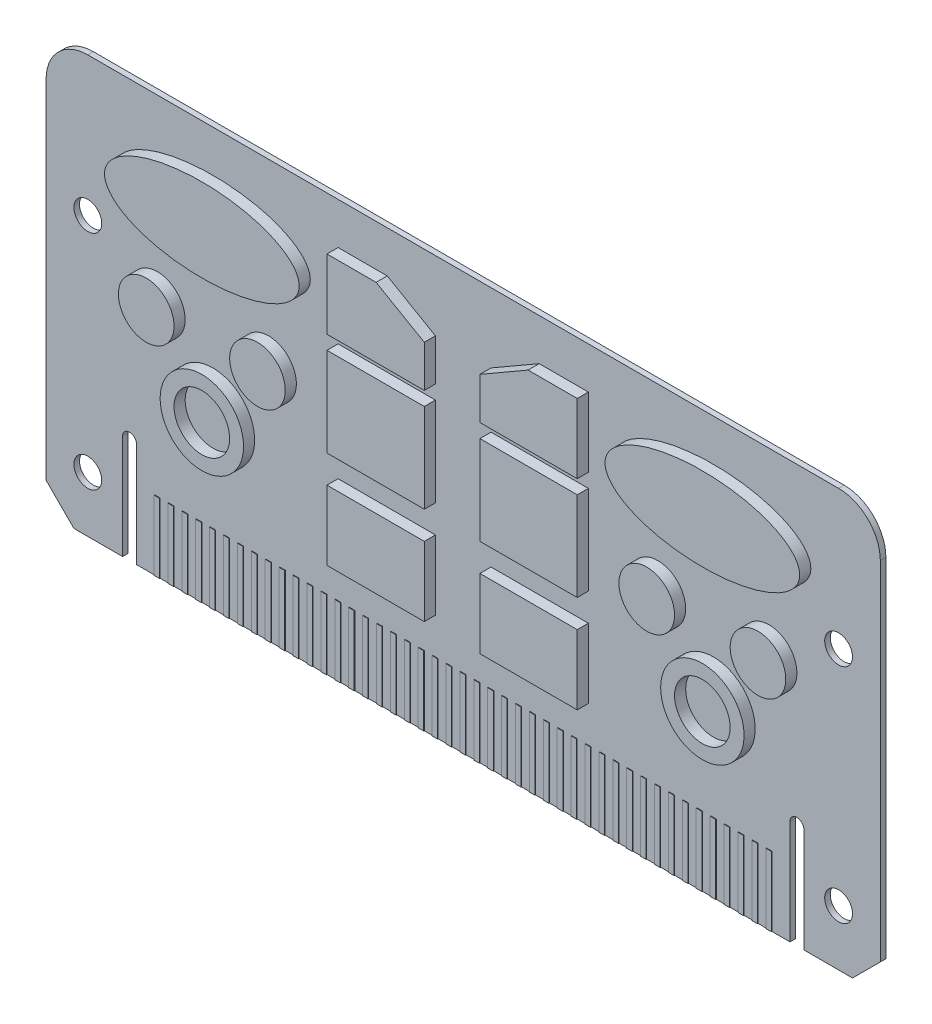
SolidWorks part; units mm, degrees
ref_plane "Front" through (0, 0, 0) normal (0, 0, 1) x (1, 0, 0)
ref_plane "Top" through (0, 0, 0) normal (0, 1, 0) x (1, 0, 0)
ref_plane "Right" through (0, 0, 0) normal (1, 0, 0) x (0, 0, -1)
sketch "Sketch1" plane through (0, 0, 0) normal (0, 0, 1) x (1, 0, 0)
  line L0 (0, 0) -> (-300, 0)
  line L1 (-300, 0) -> (-300, 150)
  line L2 (-300, 150) -> (0, 150)
  line L3 (0, 150) -> (0, 0)
  dimension "D1" = 150
  dimension "D2" = 300
extrude "PCB Base" add sketch "Sketch1" against normal mid plane 2
sketch "Sketch3" plane through (0, 0, 1) normal (0, 0, 1) x (1, 0, 0)
  line L0 (-270, -37.5) -> (-270, 37.5) construction
  line L2 (-300, 0) -> (0, 0) construction
  line L3 (-272.5, -37.5) -> (-272.5, 37.5)
  line L4 (-267.5, -37.5) -> (-267.5, 37.5)
  line L5 (-300, 150) -> (-300, 0) construction
  line L6 (-150, 150) -> (-150, 0) construction
  line L7 (0, 150) -> (-300, 150) construction
  line L8 (-30, -37.5) -> (-30, 37.5) construction
  line L9 (-27.5, -37.5) -> (-27.5, 37.5)
  line L10 (-32.5, -37.5) -> (-32.5, 37.5)
  arc A0 (-272.5, -37.5) -> (-267.5, -37.5) centre (-270, -37.5) ccw
  arc A1 (-267.5, 37.5) -> (-272.5, 37.5) centre (-270, 37.5) ccw
  arc A2 (-27.5, -37.5) -> (-32.5, -37.5) centre (-30, -37.5) cw
  arc A3 (-32.5, 37.5) -> (-27.5, 37.5) centre (-30, 37.5) cw
  point P4 (-270, 0)
  point P17 (-30, 0)
  dimension "D2" = 30
  dimension "D1" = 2.5
  dimension "D3" = 40
extrude "Slots" cut sketch "Sketch3" against normal up to next
sketch "Sketch2" plane through (0, 0, 0) normal (0, 0, 1) x (1, 0, 0)
  line L0 (-27.5, 0) -> (0, 0) construction
  line L1 (0, 0) -> (0, 150) construction
  line L2 (-267.5, 0) -> (-32.5, 0) construction
  line L3 (-150, 150) -> (-150, 0) construction
  line L4 (0, 150) -> (-300, 150) construction
  line L5 (-177.3205, 135) -> (-160, 125)
  line L6 (-195, 135) -> (-177.3205, 135)
  line L7 (-195, 135) -> (-195, 110)
  line L8 (-195, 110) -> (-160, 110)
  line L9 (-160, 125) -> (-160, 110)
  line L10 (-195, 105) -> (-160, 105)
  line L11 (-195, 105) -> (-195, 73)
  line L12 (-195, 73) -> (-160, 73)
  line L13 (-160, 105) -> (-160, 73)
  line L14 (-195, 63) -> (-160, 63)
  line L15 (-195, 63) -> (-195, 38)
  line L16 (-195, 38) -> (-160, 38)
  line L17 (-160, 63) -> (-160, 38)
  line L18 (-140, 63) -> (-140, 38)
  line L19 (-105, 38) -> (-140, 38)
  line L20 (-105, 63) -> (-105, 38)
  line L21 (-105, 63) -> (-140, 63)
  line L22 (-140, 105) -> (-140, 73)
  line L23 (-105, 73) -> (-140, 73)
  line L24 (-105, 105) -> (-105, 73)
  line L25 (-105, 105) -> (-140, 105)
  line L26 (-140, 125) -> (-140, 110)
  line L27 (-105, 110) -> (-140, 110)
  line L28 (-105, 135) -> (-105, 110)
  line L29 (-105, 135) -> (-122.6795, 135)
  line L30 (-122.6795, 135) -> (-140, 125)
  circle A0 centre (-260, 85) radius 10
  circle A1 centre (-220, 85) radius 10
  circle A2 centre (-240, 60) radius 15
  circle A3 centre (-240, 60) radius 10
  circle A4 centre (-60, 60) radius 10
  circle A5 centre (-60, 60) radius 15
  circle A6 centre (-80, 85) radius 10
  circle A7 centre (-40, 85) radius 10
  ellipse E0 centre (-240, 120) end of major axis (-275, 120) minor radius 15
  ellipse E1 centre (-60, 120) end of major axis (-95, 120) minor radius 15
  dimension "D1" = 70
  dimension "D3" = 240
  dimension "D5" = 220
  dimension "D6" = 40
  dimension "D7" = 85
  dimension "D8" = 20
  dimension "D11" = 30
  dimension "D12" = 5
  dimension "D2" = 30
  dimension "D4" = 120
  dimension "D9" = 240
  dimension "D10" = 60
  dimension "D13" = 160
  dimension "D14" = 15
  dimension "D15" = 135
  dimension "D16" = 195
  dimension "D17" = 105
  dimension "D18" = 10
  dimension "D19" = 32
  dimension "D20" = 25
  dimension "D21" = 110
  dimension "D22" = 120
extrude "Surface Chips" add sketch "Sketch2" along normal blind 5
mirror "Mirror Chips" about plane through (0, 0, 0) normal (0, 0, 1) of "Surface Chips"
sketch "Sketch4" plane through (0, 0, 1) normal (0, 0, 1) x (1, 0, 0)
  line L1 (-261, 0) -> (-259, 0)
  line L2 (-261, 0) -> (-261, 25)
  line L3 (-261, 25) -> (-259, 25)
  line L4 (-259, 0) -> (-259, 25)
  line L6 (-256, 25) -> (-254, 25)
  line L7 (-256, 0) -> (-256, 25)
  line L8 (-254, 0) -> (-254, 25)
  line L9 (-256, 0) -> (-254, 0)
  line L10 (-251, 25) -> (-249, 25)
  line L11 (-251, 0) -> (-251, 25)
  line L12 (-249, 0) -> (-249, 25)
  line L13 (-251, 0) -> (-249, 0)
  line L14 (-246, 25) -> (-244, 25)
  line L15 (-246, 0) -> (-246, 25)
  line L16 (-244, 0) -> (-244, 25)
  line L17 (-246, 0) -> (-244, 0)
  line L18 (-241, 25) -> (-239, 25)
  line L19 (-241, 0) -> (-241, 25)
  line L20 (-239, 0) -> (-239, 25)
  line L21 (-241, 0) -> (-239, 0)
  line L22 (-236, 25) -> (-234, 25)
  line L23 (-236, 0) -> (-236, 25)
  line L24 (-234, 0) -> (-234, 25)
  line L25 (-236, 0) -> (-234, 0)
  line L26 (-231, 25) -> (-229, 25)
  line L27 (-231, 0) -> (-231, 25)
  line L28 (-229, 0) -> (-229, 25)
  line L29 (-231, 0) -> (-229, 0)
  line L30 (-226, 25) -> (-224, 25)
  line L31 (-226, 0) -> (-226, 25)
  line L32 (-224, 0) -> (-224, 25)
  line L33 (-226, 0) -> (-224, 0)
  line L34 (-221, 25) -> (-219, 25)
  line L35 (-221, 0) -> (-221, 25)
  line L36 (-219, 0) -> (-219, 25)
  line L37 (-221, 0) -> (-219, 0)
  line L38 (-216, 25) -> (-214, 25)
  line L39 (-216, 0) -> (-216, 25)
  line L40 (-214, 0) -> (-214, 25)
  line L41 (-216, 0) -> (-214, 0)
  line L42 (-211, 25) -> (-209, 25)
  line L43 (-211, 0) -> (-211, 25)
  line L44 (-209, 0) -> (-209, 25)
  line L45 (-211, 0) -> (-209, 0)
  line L46 (-206, 25) -> (-204, 25)
  line L47 (-206, 0) -> (-206, 25)
  line L48 (-204, 0) -> (-204, 25)
  line L49 (-206, 0) -> (-204, 0)
  line L50 (-201, 25) -> (-199, 25)
  line L51 (-201, 0) -> (-201, 25)
  line L52 (-199, 0) -> (-199, 25)
  line L53 (-201, 0) -> (-199, 0)
  line L54 (-196, 25) -> (-194, 25)
  line L55 (-196, 0) -> (-196, 25)
  line L56 (-194, 0) -> (-194, 25)
  line L57 (-196, 0) -> (-194, 0)
  line L58 (-191, 25) -> (-189, 25)
  line L59 (-191, 0) -> (-191, 25)
  line L60 (-189, 0) -> (-189, 25)
  line L61 (-191, 0) -> (-189, 0)
  line L62 (-186, 25) -> (-184, 25)
  line L63 (-186, 0) -> (-186, 25)
  line L64 (-184, 0) -> (-184, 25)
  line L65 (-186, 0) -> (-184, 0)
  line L66 (-181, 25) -> (-179, 25)
  line L67 (-181, 0) -> (-181, 25)
  line L68 (-179, 0) -> (-179, 25)
  line L69 (-181, 0) -> (-179, 0)
  line L70 (-176, 25) -> (-174, 25)
  line L71 (-176, 0) -> (-176, 25)
  line L72 (-174, 0) -> (-174, 25)
  line L73 (-176, 0) -> (-174, 0)
  line L74 (-171, 25) -> (-169, 25)
  line L75 (-171, 0) -> (-171, 25)
  line L76 (-169, 0) -> (-169, 25)
  line L77 (-171, 0) -> (-169, 0)
  line L78 (-166, 25) -> (-164, 25)
  line L79 (-166, 0) -> (-166, 25)
  line L80 (-164, 0) -> (-164, 25)
  line L81 (-166, 0) -> (-164, 0)
  line L82 (-161, 25) -> (-159, 25)
  line L83 (-161, 0) -> (-161, 25)
  line L84 (-159, 0) -> (-159, 25)
  line L85 (-161, 0) -> (-159, 0)
  line L86 (-156, 25) -> (-154, 25)
  line L87 (-156, 0) -> (-156, 25)
  line L88 (-154, 0) -> (-154, 25)
  line L89 (-156, 0) -> (-154, 0)
  line L90 (-151, 25) -> (-149, 25)
  line L91 (-151, 0) -> (-151, 25)
  line L92 (-149, 0) -> (-149, 25)
  line L93 (-151, 0) -> (-149, 0)
  line L94 (-146, 25) -> (-144, 25)
  line L95 (-146, 0) -> (-146, 25)
  line L96 (-144, 0) -> (-144, 25)
  line L97 (-146, 0) -> (-144, 0)
  line L98 (-141, 25) -> (-139, 25)
  line L99 (-141, 0) -> (-141, 25)
  line L100 (-139, 0) -> (-139, 25)
  line L101 (-141, 0) -> (-139, 0)
  line L102 (-136, 25) -> (-134, 25)
  line L103 (-136, 0) -> (-136, 25)
  line L104 (-134, 0) -> (-134, 25)
  line L105 (-136, 0) -> (-134, 0)
  line L106 (-131, 25) -> (-129, 25)
  line L107 (-131, 0) -> (-131, 25)
  line L108 (-129, 0) -> (-129, 25)
  line L109 (-131, 0) -> (-129, 0)
  line L110 (-126, 25) -> (-124, 25)
  line L111 (-126, 0) -> (-126, 25)
  line L112 (-124, 0) -> (-124, 25)
  line L113 (-126, 0) -> (-124, 0)
  line L114 (-121, 25) -> (-119, 25)
  line L115 (-121, 0) -> (-121, 25)
  line L116 (-119, 0) -> (-119, 25)
  line L117 (-121, 0) -> (-119, 0)
  line L118 (-116, 25) -> (-114, 25)
  line L119 (-116, 0) -> (-116, 25)
  line L120 (-114, 0) -> (-114, 25)
  line L121 (-116, 0) -> (-114, 0)
  line L122 (-111, 25) -> (-109, 25)
  line L123 (-111, 0) -> (-111, 25)
  line L124 (-109, 0) -> (-109, 25)
  line L125 (-111, 0) -> (-109, 0)
  line L126 (-106, 25) -> (-104, 25)
  line L127 (-106, 0) -> (-106, 25)
  line L128 (-104, 0) -> (-104, 25)
  line L129 (-106, 0) -> (-104, 0)
  line L130 (-101, 25) -> (-99, 25)
  line L131 (-101, 0) -> (-101, 25)
  line L132 (-99, 0) -> (-99, 25)
  line L133 (-101, 0) -> (-99, 0)
  line L134 (-96, 25) -> (-94, 25)
  line L135 (-96, 0) -> (-96, 25)
  line L136 (-94, 0) -> (-94, 25)
  line L137 (-96, 0) -> (-94, 0)
  line L138 (-91, 25) -> (-89, 25)
  line L139 (-91, 0) -> (-91, 25)
  line L140 (-89, 0) -> (-89, 25)
  line L141 (-91, 0) -> (-89, 0)
  line L142 (-86, 25) -> (-84, 25)
  line L143 (-86, 0) -> (-86, 25)
  line L144 (-84, 0) -> (-84, 25)
  line L145 (-86, 0) -> (-84, 0)
  line L146 (-81, 25) -> (-79, 25)
  line L147 (-81, 0) -> (-81, 25)
  line L148 (-79, 0) -> (-79, 25)
  line L149 (-81, 0) -> (-79, 0)
  line L150 (-76, 25) -> (-74, 25)
  line L151 (-76, 0) -> (-76, 25)
  line L152 (-74, 0) -> (-74, 25)
  line L153 (-76, 0) -> (-74, 0)
  line L154 (-71, 25) -> (-69, 25)
  line L155 (-71, 0) -> (-71, 25)
  line L156 (-69, 0) -> (-69, 25)
  line L157 (-71, 0) -> (-69, 0)
  line L158 (-66, 25) -> (-64, 25)
  line L159 (-66, 0) -> (-66, 25)
  line L160 (-64, 0) -> (-64, 25)
  line L161 (-66, 0) -> (-64, 0)
  line L162 (-61, 25) -> (-59, 25)
  line L163 (-61, 0) -> (-61, 25)
  line L164 (-59, 0) -> (-59, 25)
  line L165 (-61, 0) -> (-59, 0)
  line L166 (-56, 25) -> (-54, 25)
  line L167 (-56, 0) -> (-56, 25)
  line L168 (-54, 0) -> (-54, 25)
  line L169 (-56, 0) -> (-54, 0)
  line L170 (-51, 25) -> (-49, 25)
  line L171 (-51, 0) -> (-51, 25)
  line L172 (-49, 0) -> (-49, 25)
  line L173 (-51, 0) -> (-49, 0)
  line L174 (-46, 25) -> (-44, 25)
  line L175 (-46, 0) -> (-46, 25)
  line L176 (-44, 0) -> (-44, 25)
  line L177 (-46, 0) -> (-44, 0)
  line L178 (-41, 25) -> (-39, 25)
  line L179 (-41, 0) -> (-41, 25)
  line L180 (-39, 0) -> (-39, 25)
  line L181 (-41, 0) -> (-39, 0)
  line L183 (-267.5, 0) -> (-267.5, 37.5) construction
  line L185 (-267.5, 0) -> (-32.5, 0) construction
  dimension "D1" = 2
  dimension "D2" = 6.5
  dimension "D3" = 25
  dimension "D5" = 3
  dimension "D4" = 45
extrude "Contacts" add sketch "Sketch4" along normal blind 0.2
hole_wizard "Ø10.0mm Dowel Hole1" positions "Sketch6" profile "Sketch5" hole size "Ø10.0" standard "ANSI Metric" end condition through all
sketch "Sketch6" plane through (0, 0, 1) normal (0, 0, 1) x (1, 0, 0)
  line L3 (-300, 150) -> (-300, 0) construction
  line L4 (-300, 0) -> (-272.5, 0) construction
  point P4 (-285, 20)
  point P16 (-15, 20)
  point P22 (-285, 100)
  point P24 (-15, 100)
  dimension "D1" = 15
  dimension "D2" = 285
  dimension "D3" = 20
  dimension "D4" = 100
sketch "Sketch5" plane through (-285, 20, 1) normal (1, 0, 0) x (0, -1, 0)
  line L0 (0, 0) -> (0, 6)
  line L1 (0, 6) -> (5, 6)
  line L2 (5, 6) -> (5, 0)
  line L5 (5, 0) -> (0, 0)
  line L11 (0, -6.35) -> (0, 107.95) construction
  dimension "Thru Hole Dia." = 10
  dimension "Thru Hole Depth" = 6
chamfer "Chamfer1" distance 10 angle 45 2 edges at (0, 0, 0) (-300, 0, 0)
fillet "Fillet1" radius 15 2 edges at (0, 150, 0) (-300, 150, 0)
